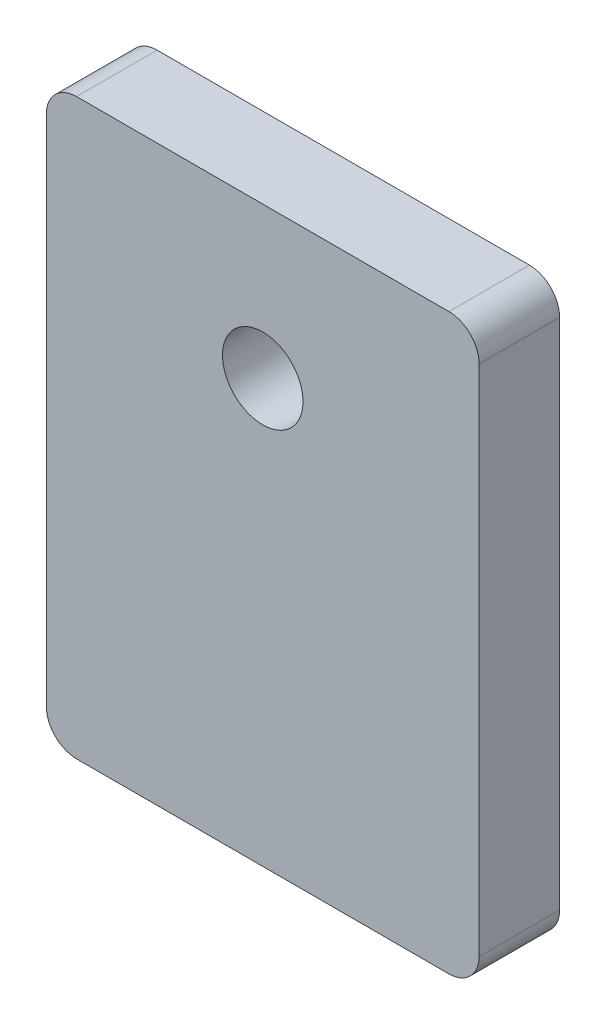
SolidWorks part; units mm, degrees
ref_plane "Front Plane" through (0, 0, 0) normal (0, 0, 1) x (1, 0, 0)
ref_plane "Top Plane" through (0, 0, 0) normal (0, 1, 0) x (1, 0, 0)
ref_plane "Right Plane" through (0, 0, 0) normal (1, 0, 0) x (0, 0, -1)
sketch "Sketch1" plane through (0, 0, 0) normal (0, 0, 1) x (1, 0, 0)
  line L1 (-21.5, -28.5) -> (21.5, -28.5)
  line L2 (-21.5, -28.5) -> (-21.5, 28.5)
  line L3 (-21.5, 28.5) -> (21.5, 28.5)
  line L4 (21.5, -28.5) -> (21.5, 28.5)
  line L5 (-21.5, -28.5) -> (21.5, 28.5) construction
  line L6 (-21.5, 28.5) -> (21.5, -28.5) construction
  point P0 (0, 0)
  dimension "D1" = 43
  dimension "D2" = 57
extrude "Boss-Extrude1" add sketch "Sketch1" along normal mid plane 8
sketch "Sketch2" plane through (0, 0, 4) normal (0, 0, 1) x (1, 0, 0)
  line L0 (0, 13.5) -> (0, -28.5) construction
  line L10 (-21.5, -28.5) -> (21.5, -28.5) construction
  circle A4 centre (0, 13.5) radius 4
  point P13 (0, 13.5)
  dimension "D5" = 8
  dimension "D1" = 42
extrude "Cut-Extrude1" cut sketch "Sketch2" against normal through all
fillet "Fillet1" radius 3 4 edges at (21.5, -28.5, 0) (-21.5, -28.5, 0) (-21.5, 28.5, 0) (21.5, 28.5, 0)
